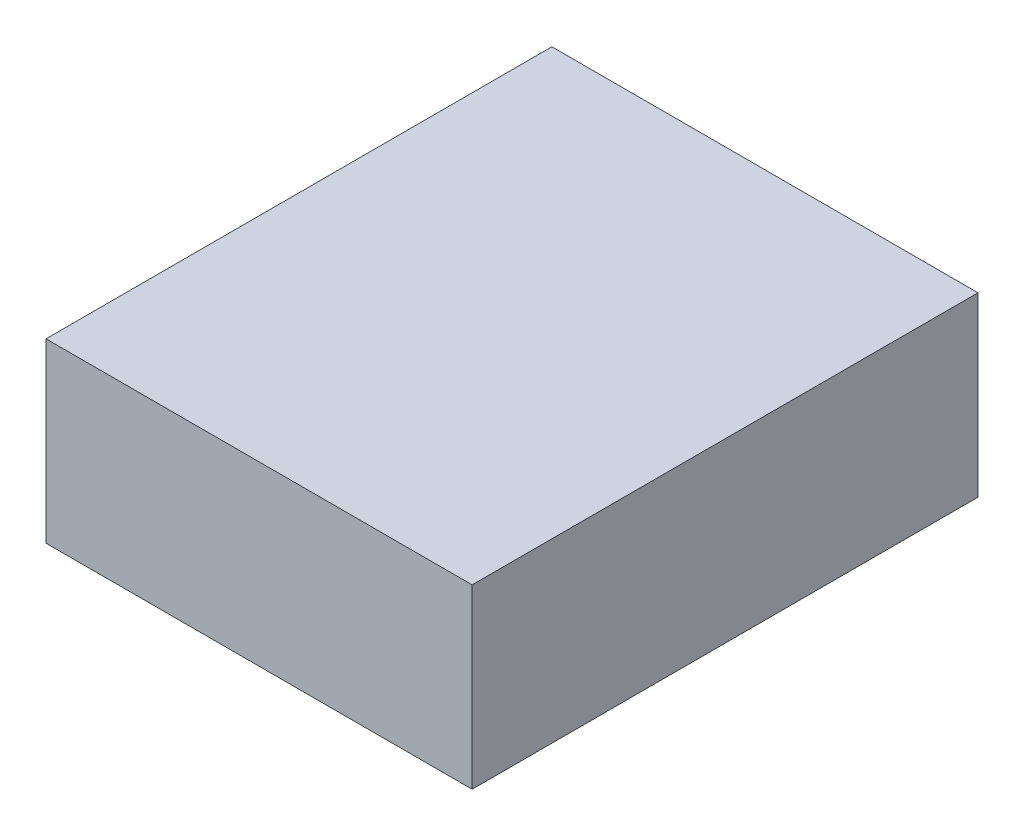
SolidWorks part; units mm, degrees
ref_plane "Front Plane" through (0, 0, 0) normal (0, 0, 1) x (1, 0, 0)
ref_plane "Top Plane" through (0, 0, 0) normal (0, 1, 0) x (1, 0, 0)
ref_plane "Right Plane" through (0, 0, 0) normal (1, 0, 0) x (0, 0, -1)
sketch "Sketch1" plane through (0, 0, 0) normal (0, 1, 0) x (1, 0, 0)
  line L1 (0, 0) -> (-67.8688, 0)
  line L2 (0, 0) -> (0, -80.5688)
  line L3 (0, -80.5688) -> (-67.8688, -80.5688)
  line L4 (-67.8688, 0) -> (-67.8688, -80.5688)
  dimension "D1" = 67.8688
  dimension "D2" = 80.5688
extrude "Boss-Extrude1" add sketch "Sketch1" along normal blind 28.194
